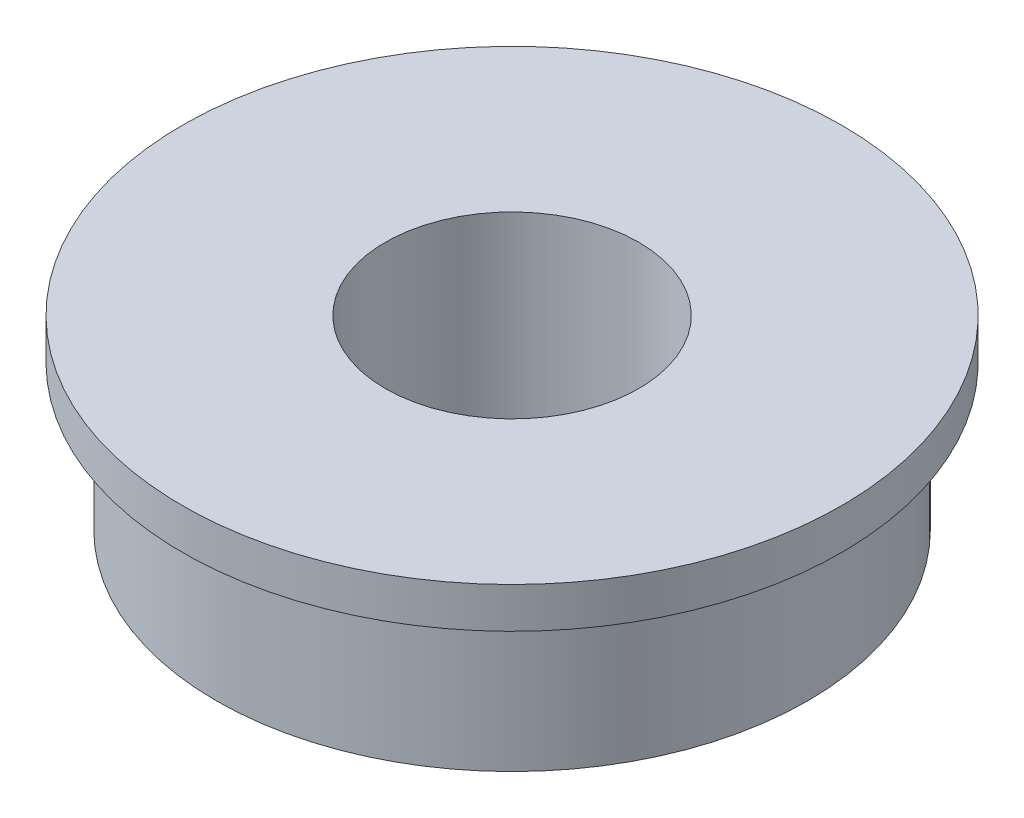
SolidWorks part; units mm, degrees
ref_plane "Front Plane" through (0, 0, 0) normal (0, 0, 1) x (1, 0, 0)
ref_plane "Top Plane" through (0, 0, 0) normal (0, 1, 0) x (1, 0, 0)
ref_plane "Right Plane" through (0, 0, 0) normal (1, 0, 0) x (0, 0, -1)
sketch "Sketch1" plane through (0, 0, 0) normal (0, 1, 0) x (1, 0, 0)
  circle A0 centre (-11.5886, 0) radius 11.1125
  dimension "D1" = 22.225
extrude "Boss-Extrude1" add sketch "Sketch1" along normal blind 5.461
sketch "Sketch2" plane through (0, 5.461, 0) normal (0, 1, 0) x (1, 0, 0)
  circle A0 centre (-11.5886, 0) radius 12.3825
  dimension "D1" = 24.765
extrude "Boss-Extrude2" add sketch "Sketch2" along normal blind 1.524
sketch "Sketch3" plane through (0, 6.985, 0) normal (0, 1, 0) x (1, 0, 0)
  circle A0 centre (-11.5886, 0) radius 4.7625
  dimension "D1" = 9.525
extrude "Cut-Extrude1" cut sketch "Sketch3" against normal blind 16.764
